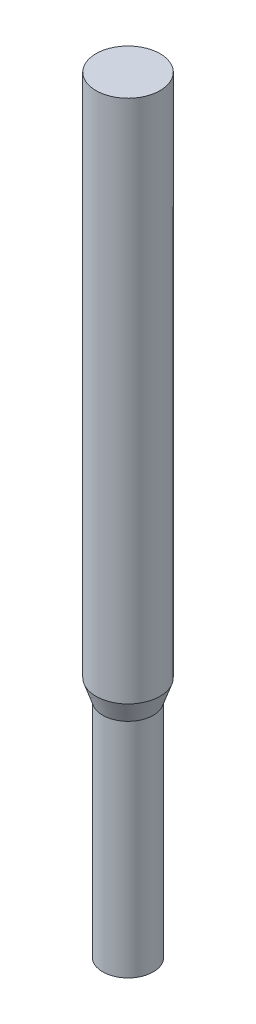
SolidWorks part; units mm, degrees
ref_plane "Front Plane" through (0, 0, 0) normal (0, 0, 1) x (1, 0, 0)
ref_plane "Top Plane" through (0, 0, 0) normal (0, 1, 0) x (1, 0, 0)
ref_plane "Right Plane" through (0, 0, 0) normal (1, 0, 0) x (0, 0, -1)
sketch "Sketch1" plane through (0, 0, 0) normal (0, 0, 1) x (1, 0, 0)
  line L0 (0, 0) -> (-1.5875, 0)
  line L1 (-1.5875, 0) -> (-1.5875, -26)
  line L2 (-1.5875, -26) -> (-1.25, -26.9839)
  line L3 (-1.25, -26.9839) -> (-1.25, -38)
  line L4 (-1.25, -38) -> (0, -38)
  line L5 (0, -38) -> (0, 0) construction
  line L6 (0, 0) -> (0, -38)
  dimension "D1" = 3.175
  dimension "D2" = 38
  dimension "D3" = 2.5
  dimension "D4" = 12
revolve "Revolve1" add sketch "Sketch1" angle 360 about L5
